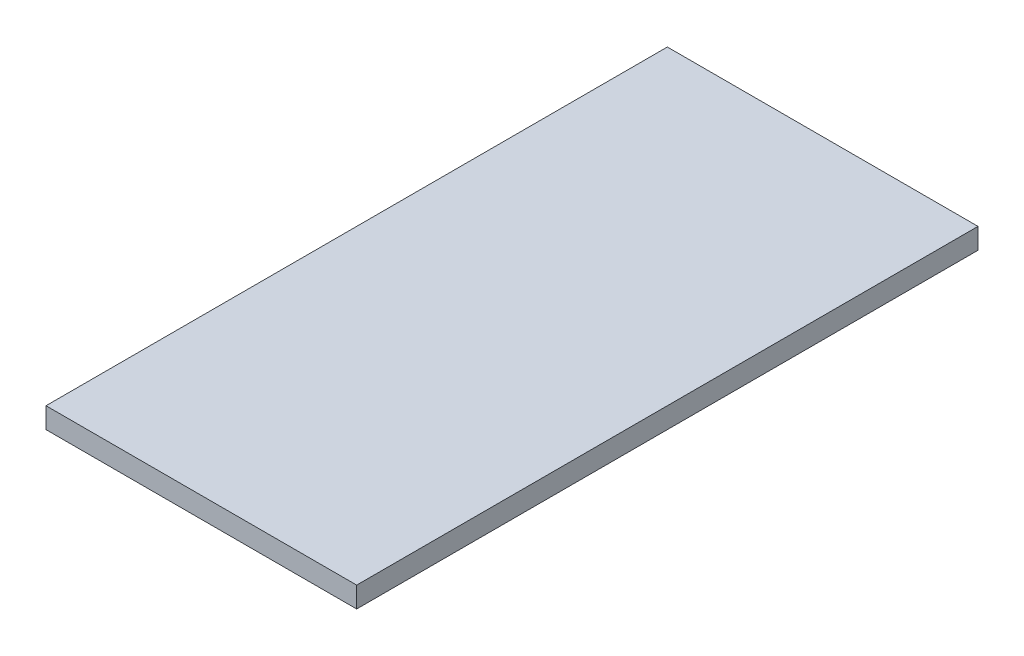
SolidWorks part; units mm, degrees
ref_plane "Front Plane" through (0, 0, 0) normal (0, 0, 1) x (1, 0, 0)
ref_plane "Top Plane" through (0, 0, 0) normal (0, 1, 0) x (1, 0, 0)
ref_plane "Right Plane" through (0, 0, 0) normal (1, 0, 0) x (0, 0, -1)
sketch "Base Sketch" plane through (0, 0, 0) normal (0, 1, 0) x (1, 0, 0)
  line L1 (75, -150) -> (-75, -150)
  line L2 (75, -150) -> (75, 150)
  line L3 (75, 150) -> (-75, 150)
  line L4 (-75, -150) -> (-75, 150)
  line L5 (75, -150) -> (-75, 150) construction
  line L6 (75, 150) -> (-75, -150) construction
  point P0 (0, 0)
  dimension "L" = 150
  dimension "W" = 300
extrude "Boss-Extrude1" add sketch "Base Sketch" along normal blind 10
